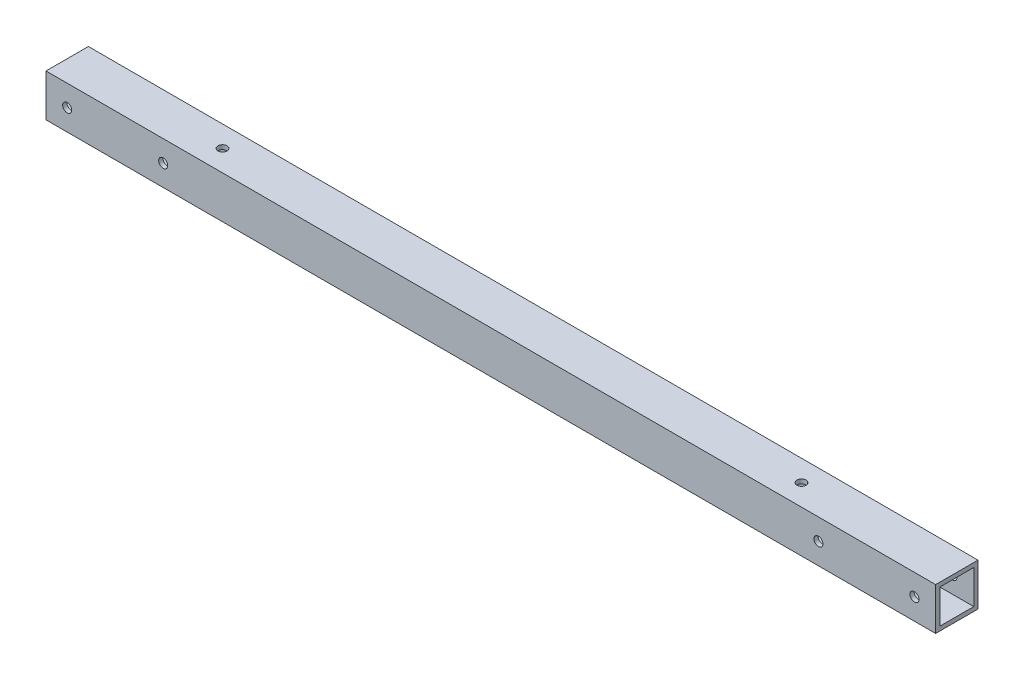
SolidWorks part; units mm, degrees
ref_plane "正面" through (0, 0, 0) normal (0, 0, 1) x (1, 0, 0)
ref_plane "平面" through (0, 0, 0) normal (0, 1, 0) x (1, 0, 0)
ref_plane "右側面" through (0, 0, 0) normal (1, 0, 0) x (0, 0, -1)
sketch "ｽｹｯﾁ2" plane through (0, 0, 0) normal (0, 0, 1) x (1, 0, 0)
  line L0 (0, -7.5) -> (315, -7.5) construction
  line L1 (0, 0) -> (315, 0)
  line L2 (0, 0) -> (0, -15)
  line L3 (0, -15) -> (315, -15)
  line L4 (315, 0) -> (315, -15)
  circle A0 centre (7.5, -7.5) radius 1.6
  circle A1 centre (41.5, -7.5) radius 1.6
  circle A2 centre (273.5, -7.5) radius 1.6
  circle A3 centre (307.5, -7.5) radius 1.6
  dimension "D1" = 7.5
  dimension "D3" = 34
  dimension "D4" = 3.2
  dimension "D5" = 7.5
  dimension "D6" = 34
  dimension "D7" = 300
  dimension "D2" = 15
extrude "ﾎﾞｽ - 押し出し1" add sketch "ｽｹｯﾁ2" along normal blind 15
sketch "ｽｹｯﾁ3" plane through (315, 0, 0) normal (1, 0, 0) x (0, 0, -1)
  line L8 (-1.5, -13.5) -> (-1.5, -1.5)
  line L9 (-1.5, -1.5) -> (-13.5, -1.5)
  line L10 (-13.5, -1.5) -> (-13.5, -13.5)
  line L11 (-13.5, -13.5) -> (-1.5, -13.5)
  line L12 (-1.5, -13.5) -> (-1.5, -1.5)
  line L13 (-1.5, -1.5) -> (-13.5, -1.5)
  line L14 (-13.5, -1.5) -> (-13.5, -13.5)
  line L15 (-13.5, -13.5) -> (-1.5, -13.5)
  dimension "D1" = 1.5
extrude "ｶｯﾄ - 押し出し1" cut sketch "ｽｹｯﾁ3" against normal through all
sketch "ｽｹｯﾁ4" plane through (0, 0, 0) normal (0, 1, 0) x (1, 0, 0)
  line L0 (315, -7.5) -> (0, -7.5) construction
  line L1 (315, -15) -> (315, 0) construction
  line L2 (0, -15) -> (0, 0) construction
  circle A0 centre (55, -7.5) radius 1.6
  circle A1 centre (260, -7.5) radius 1.6
  dimension "D1" = 55
  dimension "D2" = 55
  dimension "D3" = 3.2
extrude "ｶｯﾄ - 押し出し2" cut sketch "ｽｹｯﾁ4" against normal through all
